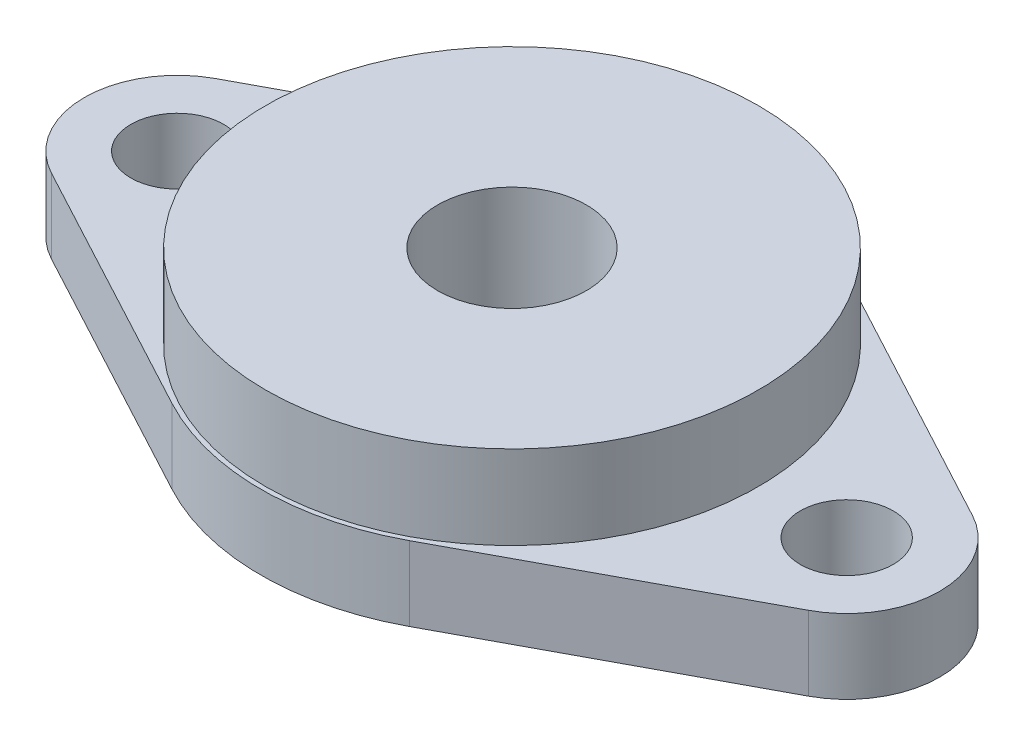
SolidWorks part; units mm, degrees
material "AISI 304"
ref_plane "前视基准面" through (0, 0, 0) normal (0, 0, 1) x (1, 0, 0)
ref_plane "上视基准面" through (0, 0, 0) normal (0, 1, 0) x (1, 0, 0)
ref_plane "右视基准面" through (0, 0, 0) normal (1, 0, 0) x (0, 0, -1)
sketch "草图1" plane through (0, 0, 0) normal (0, 1, 0) x (1, 0, 0)
  line L0 (-11.7344, 0) -> (21.6403, 0) construction
  line L1 (0, 17.054) -> (0, -18.4858) construction
  line L2 (20.3611, -4.4074) -> (6.375, -11.9)
  line L3 (-20.3611, -4.4074) -> (-6.375, -11.9)
  line L7 (20.3611, 4.4074) -> (6.375, 11.9)
  line L10 (-20.3611, 4.4074) -> (-6.375, 11.9)
  circle A0 centre (0, 0) radius 4
  circle A2 centre (18, 0) radius 2.5
  arc A5 (20.3611, -4.4074) -> (20.3611, 4.4074) centre (18, 0) ccw
  arc A8 (6.375, 11.9) -> (-6.375, 11.9) centre (0, 0) ccw
  circle A9 centre (-18, 0) radius 2.5
  arc A10 (6.375, -11.9) -> (-6.375, -11.9) centre (0, 0) cw
  arc A11 (-20.3611, -4.4074) -> (-20.3611, 4.4074) centre (-18, 0) cw
  dimension "D1" = 8
  dimension "D2" = 36
  dimension "D3" = 5
  dimension "D4" = 13.5
  dimension "D5" = 5
extrude "凸台-拉伸1" add sketch "草图1" along normal blind 4
sketch "草图2" plane through (0, 4, 0) normal (0, 1, 0) x (1, 0, 0)
  circle A0 centre (0, 0) radius 13.25
  circle A1 centre (0, 0) radius 4
  dimension "D1" = 26.5
  dimension "D2" = 8
extrude "凸台-拉伸2" add sketch "草图2" along normal blind 4.5
